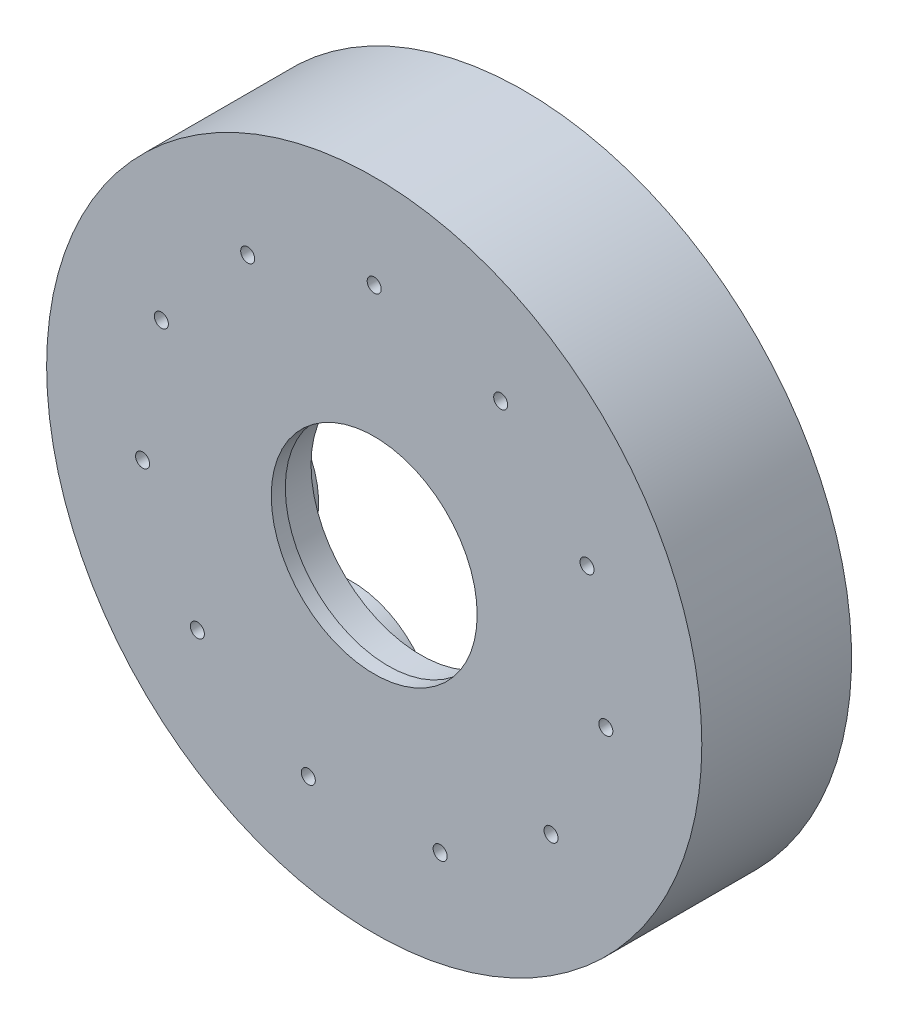
SolidWorks part; units mm, degrees
ref_plane "Front Plane" through (0, 0, 0) normal (0, 0, 1) x (1, 0, 0)
ref_plane "Top Plane" through (0, 0, 0) normal (0, 1, 0) x (1, 0, 0)
ref_plane "Right Plane" through (0, 0, 0) normal (1, 0, 0) x (0, 0, -1)
sketch "Sketch1" plane through (0, 0, 0) normal (0, 0, 1) x (1, 0, 0)
  circle A0 centre (0, 0) radius 70
  arc A2 (5.0842, 54.0498) -> (-5.0842, 54.0498) centre (0, 50) ccw
  arc A3 (33.4986, 42.7209) -> (24.9445, 48.2183) centre (27.032, 42.0627) ccw
  arc A4 (51.2775, 17.8284) -> (47.0534, 27.0778) centre (45.4816, 20.7708) ccw
  arc A5 (52.7761, -12.7245) -> (54.2232, -2.6597) centre (49.4911, -7.1157) ccw
  arc A6 (37.5187, -39.2375) -> (44.1776, -31.5527) centre (37.7875, -32.743) ccw
  arc A7 (10.3494, -53.2928) -> (20.1058, -50.428) centre (14.0866, -47.9746) ccw
  arc A8 (-20.1058, -50.428) -> (-10.3494, -53.2928) centre (-14.0866, -47.9746) ccw
  arc A9 (-44.1776, -31.5527) -> (-37.5187, -39.2375) centre (-37.7875, -32.743) ccw
  arc A10 (-54.2232, -2.6597) -> (-52.7761, -12.7245) centre (-49.4911, -7.1157) ccw
  arc A11 (-47.0534, 27.0778) -> (-51.2775, 17.8284) centre (-45.4816, 20.7708) ccw
  arc A12 (-24.9445, 48.2183) -> (-33.4986, 42.7209) centre (-27.032, 42.0627) ccw
  arc A13 (-54.2232, -2.6597) -> (-51.2775, 17.8284) centre (-67.3277, 9.6803) ccw
  arc A14 (-47.0534, 27.0778) -> (-33.4986, 42.7209) centre (-51.4061, 44.5436) ccw
  arc A15 (-24.9445, 48.2183) -> (-5.0842, 54.0498) centre (-19.1635, 65.2647) ccw
  arc A16 (5.0842, 54.0498) -> (24.9445, 48.2183) centre (19.1635, 65.2647) ccw
  arc A17 (33.4986, 42.7209) -> (47.0534, 27.0778) centre (51.4061, 44.5436) ccw
  arc A18 (51.2775, 17.8284) -> (54.2232, -2.6597) centre (67.3277, 9.6803) ccw
  arc A19 (52.7761, -12.7245) -> (44.1776, -31.5527) centre (61.8732, -28.2565) ccw
  arc A20 (37.5187, -39.2375) -> (20.1058, -50.428) centre (36.7744, -57.2221) ccw
  arc A21 (10.3494, -53.2928) -> (-10.3494, -53.2928) centre (0, -68.02) ccw
  arc A22 (-20.1058, -50.428) -> (-37.5187, -39.2375) centre (-36.7744, -57.2221) ccw
  arc A23 (-44.1776, -31.5527) -> (-52.7761, -12.7245) centre (-61.8732, -28.2565) ccw
  point P29 (0, 0)
  point P63 (0, 0)
  dimension "D1" = 140
  dimension "D2" = 13
  dimension "D5" = 11
  dimension "D4" = 11
extrude "Boss-Extrude2" add sketch "Sketch1" along normal blind 25
sketch "Sketch3" plane through (0, 0, 25) normal (0, 0, 1) x (1, 0, 0)
  circle A0 centre (0, 0) radius 70
extrude "Boss-Extrude3" add sketch "Sketch3" along normal blind 10
sketch "Sketch4" plane through (0, 0, 25) normal (0, 0, -1) x (-1, 0, 0)
  circle A0 centre (0, 0) radius 50 construction
  circle A1 centre (0, 50) radius 3
  circle A2 centre (27.032, 42.0627) radius 3
  circle A3 centre (45.4816, 20.7708) radius 3
  circle A4 centre (49.4911, -7.1157) radius 3
  circle A5 centre (37.7875, -32.743) radius 3
  circle A6 centre (14.0866, -47.9746) radius 3
  circle A7 centre (-14.0866, -47.9746) radius 3
  circle A8 centre (-37.7875, -32.743) radius 3
  circle A9 centre (-49.4911, -7.1157) radius 3
  circle A10 centre (-45.4816, 20.7708) radius 3
  circle A11 centre (-27.032, 42.0627) radius 3
  point P28 (0, 0)
  dimension "D1" = 100
  dimension "D2" = 6
  dimension "D3" = 11
extrude "Cut-Extrude1" cut sketch "Sketch4" against normal blind 4
sketch "Sketch5" plane through (0, 0, 25) normal (0, 0, -1) x (-1, 0, 0)
  circle A0 centre (0, 0) radius 23.5
  dimension "D1" = 47
extrude "Cut-Extrude2" cut sketch "Sketch5" against normal blind 7
sketch "Sketch6" plane through (0, 0, 29) normal (0, 0, -1) x (-1, 0, 0)
  circle A0 centre (0, 50) radius 1.5
  circle A1 centre (27.032, 42.0627) radius 1.5
  circle A2 centre (45.4816, 20.7708) radius 1.5
  circle A3 centre (49.4911, -7.1157) radius 1.5
  circle A4 centre (37.7875, -32.743) radius 1.5
  circle A5 centre (14.0866, -47.9746) radius 1.5
  circle A6 centre (-14.0866, -47.9746) radius 1.5
  circle A7 centre (-37.7875, -32.743) radius 1.5
  circle A8 centre (-49.4911, -7.1157) radius 1.5
  circle A9 centre (-45.4816, 20.7708) radius 1.5
  circle A10 centre (-27.032, 42.0627) radius 1.5
  point P25 (0, 0)
  dimension "D1" = 3
  dimension "D2" = 11
extrude "Cut-Extrude3" cut sketch "Sketch6" against normal blind 7
sketch "Sketch7" plane through (0, 0, 32) normal (0, 0, -1) x (-1, 0, 0)
  circle A0 centre (0, 0) radius 22
  dimension "D1" = 44
extrude "Cut-Extrude4" cut sketch "Sketch7" against normal blind 7
sketch "Sketch8" plane through (0, 0, 0) normal (0, 0, -1) x (-1, 0, 0)
  circle A0 centre (0, 0) radius 70
extrude "Cut-Extrude5" cut sketch "Sketch8" against normal blind 3
sketch "Sketch9" plane through (0, 0, 3) normal (0, 0, -1) x (-1, 0, 0)
  circle A0 centre (0, 0) radius 64 construction
  circle A1 centre (0, 64) radius 1.425
  circle A2 centre (55.4256, 32) radius 1.425
  circle A3 centre (55.4256, -32) radius 1.425
  circle A4 centre (0, -64) radius 1.425
  circle A5 centre (-55.4256, -32) radius 1.425
  circle A6 centre (-55.4256, 32) radius 1.425
  point P17 (0, 0)
  dimension "D1" = 128
  dimension "D2" = 2.85
  dimension "D3" = 6
extrude "Cut-Extrude6" cut sketch "Sketch9" against normal blind 20
